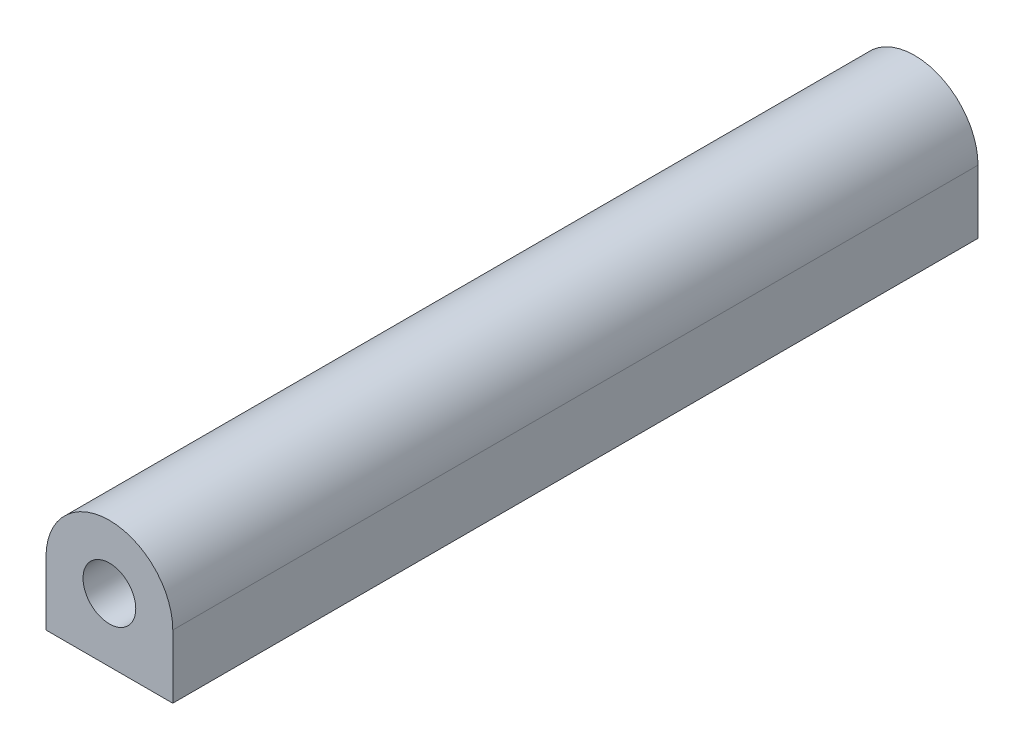
SolidWorks part; units mm, degrees
ref_plane "Front Plane" through (0, 0, 0) normal (0, 0, 1) x (1, 0, 0)
ref_plane "Top Plane" through (0, 0, 0) normal (0, 1, 0) x (1, 0, 0)
ref_plane "Right Plane" through (0, 0, 0) normal (1, 0, 0) x (0, 0, -1)
sketch "Sketch1" plane through (0, 0, 0) normal (0, 0, 1) x (1, 0, 0)
  circle A0 centre (0, 0) radius 1.425
  circle A1 centre (0, 0) radius 3.425
  dimension "D1" = 2.85
  dimension "D2" = 2
extrude "Boss-Extrude1" add sketch "Sketch1" along normal blind 43.5096 contours A1
sketch "Sketch2" plane through (0, 0, 0) normal (0, 0, -1) x (-1, 0, 0)
  circle A0 centre (0, 0) radius 1.475
  dimension "D1" = 2.95
extrude "Cut-Extrude1" cut sketch "Sketch2" against normal blind 10
sketch "Sketch3" plane through (0, 0, 43.5096) normal (0, 0, 1) x (1, 0, 0)
  circle A0 centre (0, 0) radius 1.425
  dimension "D1" = 2.85
extrude "Cut-Extrude2" cut sketch "Sketch3" against normal blind 10
sketch "Sketch4" plane through (0, 0, 43.5096) normal (0, 0, 1) x (1, 0, 0)
  line L0 (0, -3.425) -> (1.1461, -3.425)
  line L1 (3.425, 0) -> (3.425, 0.9536)
  line L3 (-3.425, 0) -> (3.425, 0)
  line L4 (-3.425, 0) -> (-3.425, -3.425)
  line L5 (-3.425, -3.425) -> (3.425, -3.425)
  line L6 (3.425, 0) -> (3.425, -3.425)
  circle A0 centre (0, 0) radius 3.425
  circle M3 centre (0, 0) radius 3.425
extrude "Boss-Extrude2" add sketch "Sketch4" against normal up to surface (43.5096 mm away) contours L4 L5 M3 | L6 L0 L5 M3 up to face at (-1.475, 0, 0)
